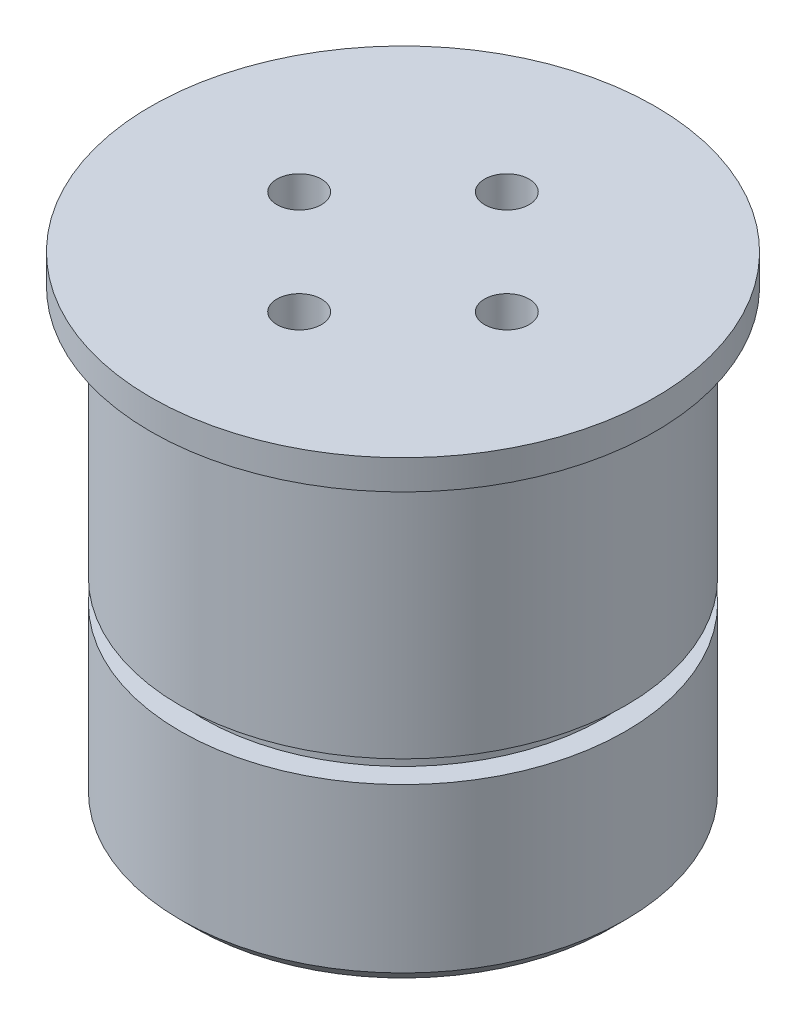
SolidWorks part; units mm, degrees
ref_plane "Спереди" through (0, 0, 0) normal (0, 0, 1) x (1, 0, 0)
ref_plane "Сверху" through (0, 0, 0) normal (0, 1, 0) x (1, 0, 0)
ref_plane "Справа" through (0, 0, 0) normal (1, 0, 0) x (0, 0, -1)
sketch "Эскиз7" plane through (0, 0, 0) normal (1, 0, 0) x (0, 0, -1)
  line L0 (10, 0) -> (15, 0)
  line L1 (15, 0) -> (15, 12)
  line L2 (15, 12) -> (13.5, 12)
  line L3 (13.5, 12) -> (13.5, 13.5)
  line L4 (13.5, 13.5) -> (15, 13.5)
  line L5 (15, 13.5) -> (15, 30.5)
  line L6 (15, 30.5) -> (17, 30.5)
  line L7 (17, 30.5) -> (17, 32.5)
  line L8 (17, 32.5) -> (0, 32.5)
  line L9 (0, 32.5) -> (0, 2.5)
  line L10 (0, 32.7031) -> (0, 2.5) construction
  line L11 (10, 0) -> (10, 2.5)
  line L12 (10, 2.5) -> (0, 2.5)
  line L13 (0, 0) -> (0, -8.1979) construction
  point P16 (0, 3.0648)
  point P17 (0, 0)
  dimension "D1" = 30
  dimension "D2" = 12
  dimension "D3" = 27
  dimension "D4" = 1.5
  dimension "D5" = 17
  dimension "D6" = 2
  dimension "D7" = 34
  dimension "D8" = 20
  dimension "D9" = 2.5
revolve "Повернуть1" add sketch "Эскиз7" angle 360 about L10
chamfer "Фаска1" distance 1 angle 45 1 edges at (0, 0, 15)
sketch "Эскиз8" plane through (0, 2.5, 0) normal (0, -1, 0) x (1, 0, 0)
  circle A0 centre (7, 0) radius 1.5
  point P2 (0, 0)
  dimension "D1" = 3
  dimension "D2" = 7
extrude "Вырез-Вытянуть1" cut sketch "Эскиз8" against normal up to surface (30 mm away) up to face at (0, 32.5, 17)
pattern_circular "Круговой массив1" count 4 every 90 about axis through (0, 0, 0) along (0, 1, 0) of "Вырез-Вытянуть1"
